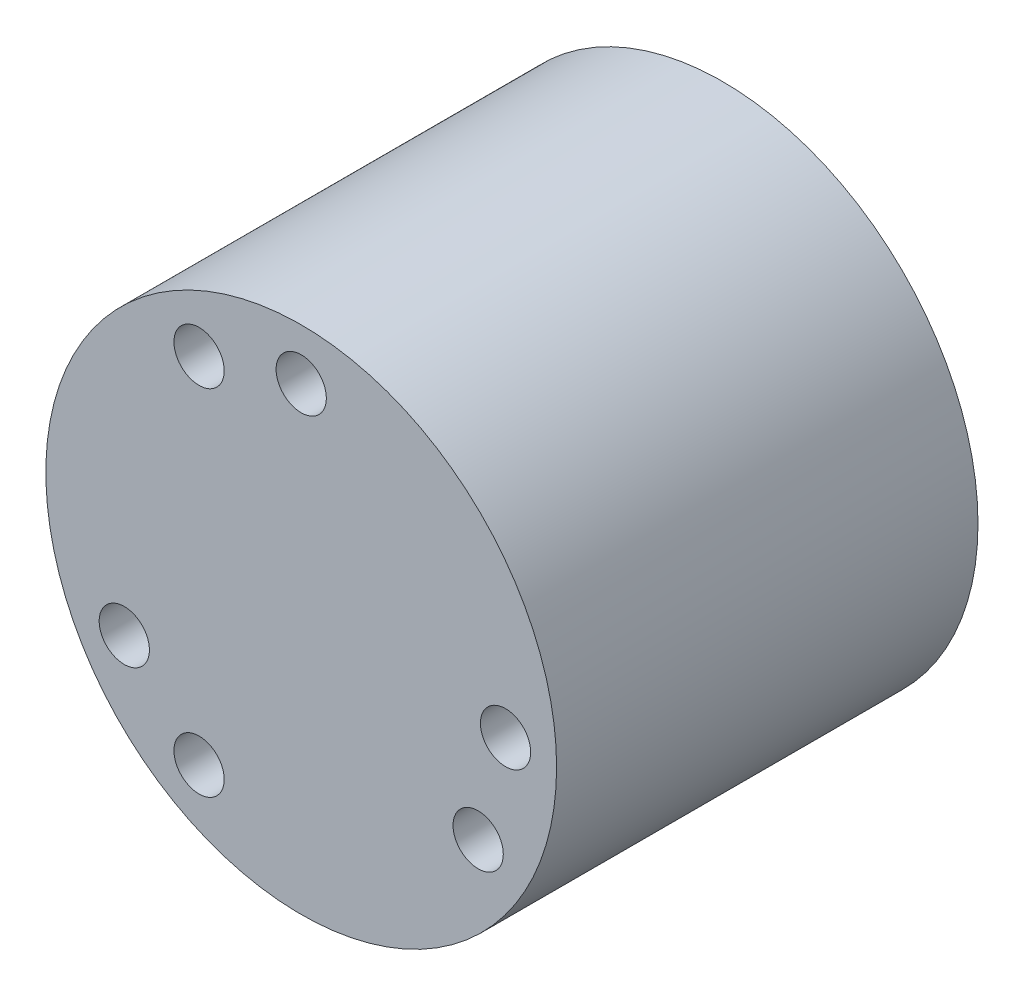
SolidWorks part; units mm, degrees
ref_plane "Front Plane" through (0, 0, 0) normal (0, 0, 1) x (1, 0, 0)
ref_plane "Top Plane" through (0, 0, 0) normal (0, 1, 0) x (1, 0, 0)
ref_plane "Right Plane" through (0, 0, 0) normal (1, 0, 0) x (0, 0, -1)
sketch "Sketch1" plane through (0, 0, 0) normal (0, 0, 1) x (1, 0, 0)
  circle A0 centre (0, 0) radius 12.7
  dimension "D1" = 25.4
extrude "Boss-Extrude1" add sketch "Sketch1" along normal blind 20.955
ref_plane "Plane1" through (0, 0, 0) normal (0, 0, -1) x (-1, 0, 0)
sketch "Sketch2" plane through (0, 0, 0) normal (0, 0, -1) x (-1, 0, 0)
  circle A0 centre (0, 10.16) radius 1.2497
  dimension "D1" = 2.4994
  dimension "D2" = 10.16
extrude "Cut-Extrude1" cut sketch "Sketch2" against normal blind 25.4
pattern_circular "CirPattern1" count 3 every 120 about axis through (0, 0, 0) along (0, 0, 1) of "Cut-Extrude1"
pattern_circular "CirPattern2" count 2 every 30 about axis through (0, 0, 0) along (0, 0, 1) of "Cut-Extrude1", "CirPattern1"
